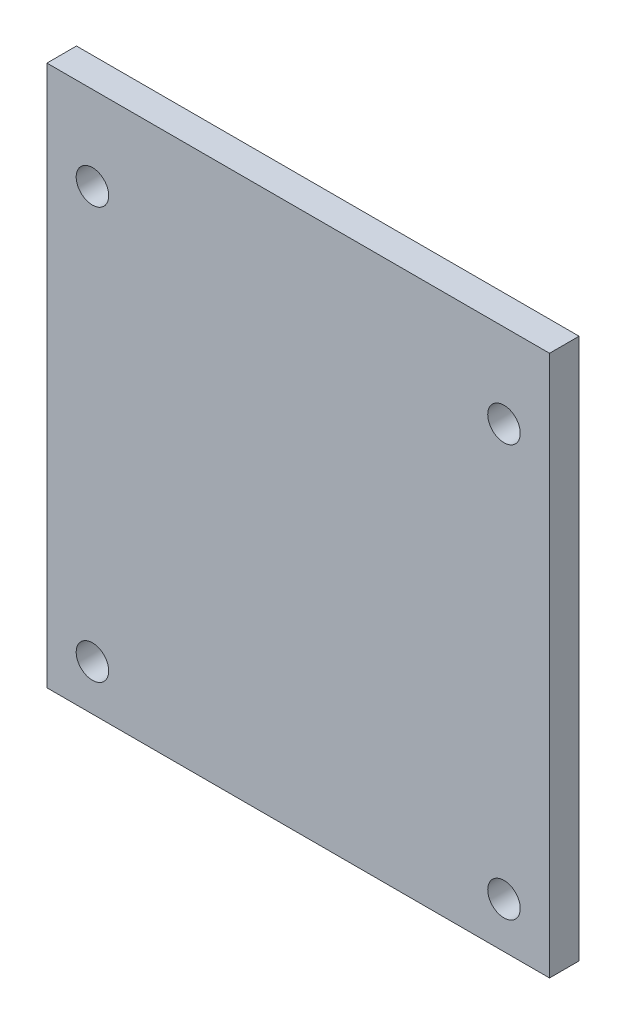
SolidWorks part; units mm, degrees
ref_plane "Спереди" through (0, 0, 0) normal (0, 0, 1) x (1, 0, 0)
ref_plane "Сверху" through (0, 0, 0) normal (0, 1, 0) x (1, 0, 0)
ref_plane "Справа" through (0, 0, 0) normal (1, 0, 0) x (0, 0, -1)
sketch "Эскиз2" plane through (0, 0, 0) normal (0, 0, 1) x (1, 0, 0)
  line L1 (0, 6.5) -> (85, 6.5)
  line L2 (0, 6.5) -> (0, -85)
  line L3 (0, -85) -> (85, -85)
  line L4 (85, 6.5) -> (85, -85)
extrude "Вытянуть1" add sketch "Эскиз2" along normal blind 5
sketch "Эскиз7" plane through (0, 0, 0) normal (0, 0, -1) x (-1, 0, 0)
  circle A0 centre (-7.7, -77.3) radius 2.75
  circle A1 centre (-77.3, -77.3) radius 2.75
  circle A2 centre (-77.3, -7.7) radius 2.75
  circle A3 centre (-7.7, -7.7) radius 2.75
extrude "Вырез-Вытянуть2" cut sketch "Эскиз7" against normal through all
